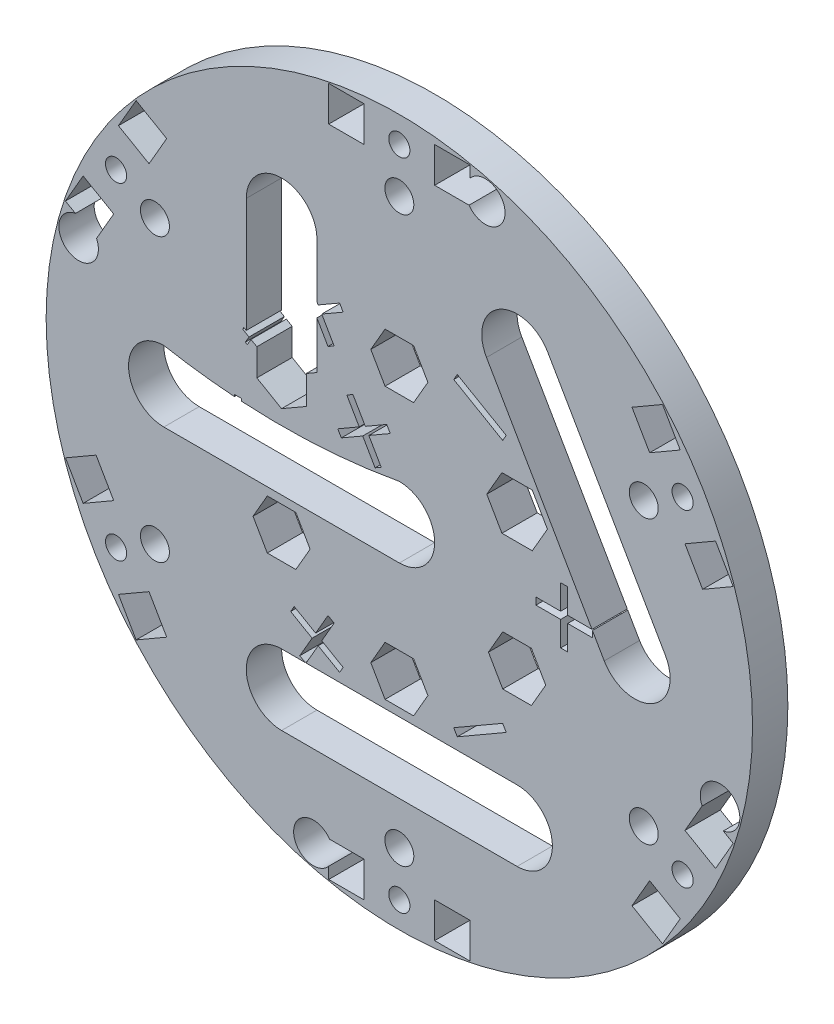
SolidWorks part; units mm, degrees
ref_plane "Plan de face" through (0, 0, 0) normal (0, 0, 1) x (1, 0, 0)
ref_plane "Plan de dessus" through (0, 0, 0) normal (0, 1, 0) x (1, 0, 0)
ref_plane "Plan de droite" through (0, 0, 0) normal (1, 0, 0) x (0, 0, -1)
sketch "Esquisse1" plane through (0, 0, 0) normal (0, 0, 1) x (1, 0, 0)
  line L0 (53.6751, 0) -> (-86.559, 0) construction
  line L1 (0, 50) -> (0, -56.2363) construction
  line L2 (0, 0) -> (70.5826, 40.7509) construction
  line L3 (0, 0) -> (-77.9761, 45.0195) construction
  line L4 (16.6667, 28.8675) -> (33.3333, 0) construction
  line L5 (20.9968, 31.3675) -> (37.6635, 2.5)
  line L6 (12.3365, 26.3675) -> (29.0032, -2.5)
  line L7 (16.6667, -28.8675) -> (-16.6667, -28.8675) construction
  line L8 (16.6667, -33.8675) -> (-16.6667, -33.8675)
  line L9 (16.6667, -23.8675) -> (-16.6667, -23.8675)
  line L10 (-33.3333, 0) -> (0, 0) construction
  line L11 (-21.6707, 12.5116) -> (-20.1709, 11.6468)
  line L12 (-33.3333, -5) -> (0, -5)
  line L13 (-16.6714, 9.6252) -> (-16.6667, 28.8675) construction
  line L14 (-21.6707, 12.5116) -> (-21.6667, 28.8687)
  line L15 (-11.6707, 12.5116) -> (-11.6667, 28.8663)
  line L16 (-13.1709, 11.6451) -> (-11.6707, 12.5116)
  line L17 (-12.6299, -9.6252) -> (-14.6507, -6.1252)
  line L18 (-14.6507, -6.1252) -> (-18.6921, -6.1252)
  line L19 (-18.6921, -6.1252) -> (-20.7128, -9.6252)
  line L20 (-20.7128, -9.6252) -> (-18.6921, -13.1252)
  line L21 (-18.6921, -13.1252) -> (-14.6507, -13.1252)
  line L22 (-14.6507, -13.1252) -> (-12.6299, -9.6252)
  line L23 (2.0207, -15.7328) -> (-2.0207, -15.7328)
  line L24 (-2.0207, -15.7328) -> (-4.0415, -19.2328)
  line L25 (-4.0415, -19.2328) -> (-2.0207, -22.7328)
  line L26 (-2.0207, -22.7328) -> (2.0207, -22.7328)
  line L27 (2.0207, -22.7328) -> (4.0415, -19.2328)
  line L28 (4.0415, -19.2328) -> (2.0207, -15.7328)
  line L29 (14.64, -6.1122) -> (12.6134, -9.6225)
  line L30 (12.6134, -9.6225) -> (14.64, -13.1328)
  line L31 (14.64, -13.1328) -> (18.6933, -13.1328)
  line L32 (18.6933, -13.1328) -> (20.72, -9.6225)
  line L33 (20.72, -9.6225) -> (18.6933, -6.1122)
  line L34 (18.6933, -6.1122) -> (14.64, -6.1122)
  line L35 (20.9633, 9.6242) -> (18.8164, 13.3427)
  line L36 (18.8164, 13.3427) -> (14.5227, 13.3427)
  line L37 (14.5227, 13.3427) -> (12.3758, 9.6242)
  line L38 (12.3758, 9.6242) -> (14.5227, 5.9057)
  line L39 (14.5227, 5.9057) -> (18.8164, 5.9057)
  line L40 (18.8164, 5.9057) -> (20.9633, 9.6242)
  line L41 (4.0415, 19.1653) -> (2.0207, 22.6653)
  line L42 (2.0207, 22.6653) -> (-2.0207, 22.6653)
  line L43 (-2.0207, 22.6653) -> (-4.0415, 19.1653)
  line L44 (-4.0415, 19.1653) -> (-2.0207, 15.6653)
  line L45 (-2.0207, 15.6653) -> (2.0207, 15.6653)
  line L46 (2.0207, 15.6653) -> (4.0415, 19.1653)
  line L47 (-20.1709, 11.6468) -> (-20.1719, 7.6054)
  line L48 (-20.1719, 7.6054) -> (-16.6724, 5.5838)
  line L49 (-16.6724, 5.5838) -> (-13.1719, 7.6036)
  line L50 (-13.1719, 7.6036) -> (-13.1709, 11.6451)
  line L52 (-16.6704, 13.6667) -> (-20.1709, 11.6468) [skipped]
  line L53 (-13.1709, 11.6451) -> (-16.6704, 13.6667) [skipped]
  circle A0 centre (0, 0) radius 50
  circle A1 centre (33.3333, 0) radius 16.6667 construction
  circle A2 centre (16.6667, -28.8675) radius 16.6667 construction
  circle A3 centre (-16.6667, -28.8675) radius 16.6667 construction
  circle A4 centre (-33.3333, 0) radius 16.6667 construction
  circle A5 centre (-16.6667, 28.8675) radius 16.6667 construction
  circle A6 centre (16.6667, 28.8675) radius 16.6667 construction
  circle A7 centre (-34.5978, 19.9751) radius 2.05
  circle A8 centre (0, 39.9502) radius 2.05
  circle A9 centre (34.5978, 19.9751) radius 2.05
  circle A10 centre (34.5978, -19.9751) radius 2.05
  circle A11 centre (0, -39.9502) radius 2.05
  circle A12 centre (-34.5978, -19.9751) radius 2.05
  arc A13 (20.9968, 31.3675) -> (12.3365, 26.3675) centre (16.6667, 28.8675) ccw
  circle A14 centre (0, 0) radius 16.6667 construction
  circle A15 centre (16.6667, -9.6225) radius 3.5103 construction
  circle A17 centre (-16.6714, -9.6252) radius 3.5 construction
  arc A18 (16.6667, -33.8675) -> (16.6667, -23.8675) centre (16.6667, -28.8675) ccw
  arc A20 (-33.3333, 5) -> (-33.3333, -5) centre (-33.3333, 0) ccw
  arc A22 (-16.6667, -23.8675) -> (-16.6667, -33.8675) centre (-16.6667, -28.8675) ccw
  circle A23 centre (0, -19.2328) radius 3.5 construction
  arc A24 (29.0032, -2.5) -> (37.6635, 2.5) centre (33.3333, 0) ccw
  circle A25 centre (16.6696, 9.6242) radius 3.7185 construction
  circle A26 centre (0, 19.1653) radius 3.5 construction
  arc A27 (0, -5) -> (0, 5) centre (0, 0) ccw
  arc A28 (-33.3333, 5) -> (0, 5) centre (-16.6667, 95.7057) ccw
  circle A29 centre (-16.6714, 9.6252) radius 3.5 construction
  arc A35 (-11.6667, 28.8663) -> (-21.6667, 28.8687) centre (-16.6667, 28.8675) ccw
  point P20 (0, 0)
  point P30 (0, 0)
  point P36 (25, 14.4338)
  point P40 (0, -28.8675)
  point P44 (-16.669, 19.2464)
  point P48 (-16.6667, 0)
  point P54 (0, 0)
  point P60 (0, 0)
  point P117 (0, 0)
  line B0 (37.597, -27.4801) -> (42.597, -18.8199) construction
  line B1 (35.4319, -26.2301) -> (32.9319, -30.5603)
  line B2 (35.4319, -26.2301) -> (39.762, -28.7301)
  line B3 (39.762, -28.7301) -> (37.262, -33.0603)
  line B4 (32.9319, -30.5603) -> (37.262, -33.0603)
  line B5 (40.4319, -17.5699) -> (42.9319, -13.2397)
  line B6 (40.4319, -17.5699) -> (44.762, -20.0699)
  line B7 (44.762, -20.0699) -> (47.262, -15.7397)
  line B8 (42.9319, -13.2397) -> (47.262, -15.7397)
  circle B9 centre (40.097, -23.15) radius 1.5
  line B10 (-5, -46.3) -> (5, -46.3) construction
  line B11 (-5, -43.8) -> (-10, -43.8)
  line B12 (-5, -43.8) -> (-5, -48.8)
  line B13 (-5, -48.8) -> (-10, -48.8)
  line B14 (-10, -43.8) -> (-10, -48.8)
  line B15 (5, -43.8) -> (10, -43.8)
  line B16 (5, -43.8) -> (5, -48.8)
  line B17 (5, -48.8) -> (10, -48.8)
  line B18 (10, -43.8) -> (10, -48.8)
  circle B19 centre (0, -46.3) radius 1.5
  line B20 (-42.597, -18.8199) -> (-37.597, -27.4801) construction
  line B21 (-40.4319, -17.5699) -> (-42.9319, -13.2397)
  line B22 (-40.4319, -17.5699) -> (-44.762, -20.0699)
  line B23 (-44.762, -20.0699) -> (-47.262, -15.7397)
  line B24 (-42.9319, -13.2397) -> (-47.262, -15.7397)
  line B25 (-35.4319, -26.2301) -> (-32.9319, -30.5603)
  line B26 (-35.4319, -26.2301) -> (-39.762, -28.7301)
  line B27 (-39.762, -28.7301) -> (-37.262, -33.0603)
  line B28 (-32.9319, -30.5603) -> (-37.262, -33.0603)
  circle B29 centre (-40.097, -23.15) radius 1.5
  line B30 (-37.597, 27.4801) -> (-42.597, 18.8199) construction
  line B31 (-35.4319, 26.2301) -> (-32.9319, 30.5603)
  line B32 (-35.4319, 26.2301) -> (-39.762, 28.7301)
  line B33 (-39.762, 28.7301) -> (-37.262, 33.0603)
  line B34 (-32.9319, 30.5603) -> (-37.262, 33.0603)
  line B35 (-40.4319, 17.5699) -> (-42.9319, 13.2397)
  line B36 (-40.4319, 17.5699) -> (-44.762, 20.0699)
  line B37 (-44.762, 20.0699) -> (-47.262, 15.7397)
  line B38 (-42.9319, 13.2397) -> (-47.262, 15.7397)
  circle B39 centre (-40.097, 23.15) radius 1.5
  line B40 (5, 46.3) -> (-5, 46.3) construction
  line B41 (5, 43.8) -> (10, 43.8)
  line B42 (5, 43.8) -> (5, 48.8)
  line B43 (5, 48.8) -> (10, 48.8)
  line B44 (10, 43.8) -> (10, 48.8)
  line B45 (-5, 43.8) -> (-10, 43.8)
  line B46 (-5, 43.8) -> (-5, 48.8)
  line B47 (-5, 48.8) -> (-10, 48.8)
  line B48 (-10, 43.8) -> (-10, 48.8)
  circle B49 centre (0, 46.3) radius 1.5
  line B50 (42.597, 18.8199) -> (37.597, 27.4801) construction
  line B51 (40.4319, 17.5699) -> (42.9319, 13.2397)
  line B52 (40.4319, 17.5699) -> (44.762, 20.0699)
  line B53 (44.762, 20.0699) -> (47.262, 15.7397)
  line B54 (42.9319, 13.2397) -> (47.262, 15.7397)
  line B55 (35.4319, 26.2301) -> (32.9319, 30.5603)
  line B56 (35.4319, 26.2301) -> (39.762, 28.7301)
  line B57 (39.762, 28.7301) -> (37.262, 33.0603)
  line B58 (32.9319, 30.5603) -> (37.262, 33.0603)
  circle B59 centre (40.097, 23.15) radius 1.5
  dimension "D1" = 6
  dimension "D2" = 30
  dimension "D4" = 6
  dimension "D5" = 10
  dimension "D6" = 46.3
  dimension "D3" = 30
  dimension "D7" = 6
sketch_block_instance "Trou M3 plots 5mm-1"
sketch_block "Trou M3 plots 5mm" parameters "D2"=3, "D1"=5, "D3"=5, "D4"=10
sketch_block_instance "Trou M3 plots 5mm-3"
sketch_block_instance "Trou M3 plots 5mm-4"
sketch_block_instance "Trou M3 plots 5mm-5"
sketch_block_instance "Trou M3 plots 5mm-6"
sketch_block_instance "Trou M3 plots 5mm-7"
extrude "Boss.-Extru.1" add sketch "Esquisse1" along normal blind 5
sketch "Sketch2" plane through (0, 0, 5) normal (0, 0, 1) x (1, 0, 0)
  line L0 (53.6751, 0) -> (-86.559, 0) construction
  line L1 (-173205.0808, -100000) -> (173275.6634, 100040.7509) construction
  arc A0 (-50, 0) -> (-25, -14.4338) centre (-33.3333, 0) ccw
  circle A1 centre (0, 0) radius 50 construction
  arc A2 (-25, -14.4338) -> (-25, -43.3013) centre (-16.6667, -28.8675) ccw
  arc A3 (-25, -43.3013) -> (-50, 0) centre (0, 0) ccw
extrude "Cut-Extrude1" [suppressed] cut sketch "Sketch2" against normal through all contours A2 A3 A0
sketch "Sketch3" plane through (0, 0, 5) normal (0, 0, 1) x (1, 0, 0)
  line L0 (53.6751, 0) -> (-86.559, 0) construction
  line L6 (16.6667, 28.8675) -> (-16.6667, -28.8675) construction
  line L7 (-23.3333, 4) -> (-22.3333, 4)
  line L8 (-23.3333, 4) -> (-23.3333, -4)
  line L9 (-23.3333, -4) -> (-22.3333, -4)
  line L10 (-22.3333, 4) -> (-22.3333, -4)
  line L11 (-16.6667, 28.8675) -> (16.6667, -28.8675) construction
  line L12 (-13.2337, 23.9214) -> (-14.0997, 23.4214)
  line L13 (-14.0997, 23.4214) -> (-12.3497, 20.3903)
  line L14 (-12.3497, 20.3903) -> (-15.3808, 18.6403)
  line L15 (-15.3808, 18.6403) -> (-14.8808, 17.7742)
  line L16 (-14.8808, 17.7742) -> (-11.8497, 19.5242)
  line L17 (-11.8497, 19.5242) -> (-10.0997, 16.4932)
  line L18 (-10.0997, 16.4932) -> (-9.2337, 16.9932)
  line L19 (-9.2337, 16.9932) -> (-10.9837, 20.0242)
  line L20 (-10.9837, 20.0242) -> (-7.9526, 21.7742)
  line L21 (-7.9526, 21.7742) -> (-8.4526, 22.6403)
  line L22 (-8.4526, 22.6403) -> (-11.4837, 20.8903)
  line L23 (-11.4837, 20.8903) -> (-13.2337, 23.9214)
  line L24 (-16.2531, 17.5593) -> (-5.3419, 23.8588) construction
  line L25 (-14.6252, 25.3316) -> (-8.4936, 14.7114) construction
  line L26 (15.1308, 18.2073) -> (14.6308, 17.3412)
  line L27 (15.1308, 18.2073) -> (8.2026, 22.2073)
  line L28 (8.2026, 22.2073) -> (7.7026, 21.3412)
  line L29 (14.6308, 17.3412) -> (7.7026, 21.3412)
  line L30 (8.2026, -22.2073) -> (7.7026, -21.3412)
  line L31 (8.2026, -22.2073) -> (15.1308, -18.2073)
  line L32 (15.1308, -18.2073) -> (14.6308, -17.3412)
  line L33 (7.7026, -21.3412) -> (14.6308, -17.3412)
  line L34 (27.3333, -0.5) -> (27.3333, 0.5)
  line L35 (27.3333, 0.5) -> (23.8333, 0.5)
  line L36 (23.8333, 0.5) -> (23.8333, 4)
  line L37 (23.8333, 4) -> (22.8333, 4)
  line L38 (22.8333, 4) -> (22.8333, 0.5)
  line L39 (22.8333, 0.5) -> (19.3333, 0.5)
  line L40 (19.3333, 0.5) -> (19.3333, -0.5)
  line L41 (19.3333, -0.5) -> (22.8333, -0.5)
  line L42 (22.8333, -0.5) -> (22.8333, -4)
  line L43 (22.8333, -4) -> (23.8333, -4)
  line L44 (23.8333, -4) -> (23.8333, -0.5)
  line L45 (23.8333, -0.5) -> (27.3333, -0.5)
  line L46 (-14.0997, -23.4214) -> (-13.2337, -23.9214)
  line L47 (-13.2337, -23.9214) -> (-11.4837, -20.8903)
  line L48 (-11.4837, -20.8903) -> (-8.4526, -22.6403)
  line L49 (-8.4526, -22.6403) -> (-7.9526, -21.7742)
  line L50 (-7.9526, -21.7742) -> (-10.9837, -20.0242)
  line L51 (-10.9837, -20.0242) -> (-9.2337, -16.9932)
  line L52 (-9.2337, -16.9932) -> (-10.0997, -16.4932)
  line L53 (-10.0997, -16.4932) -> (-11.8497, -19.5242)
  line L54 (-11.8497, -19.5242) -> (-14.8808, -17.7742)
  line L55 (-14.8808, -17.7742) -> (-15.3808, -18.6403)
  line L56 (-15.3808, -18.6403) -> (-12.3497, -20.3903)
  line L57 (-12.3497, -20.3903) -> (-14.0997, -23.4214)
  line L58 (-21.8333, 14.2784) -> (-24.4284, 9.7836) construction
  line L59 (173205.0808, -100000) -> (-173283.0568, 100045.0195) construction
  line L60 (-7.433, 11.8744) -> (-5.683, 8.8433)
  line L61 (-6.567, 12.3744) -> (-7.433, 11.8744)
  line L62 (-7.8805, 13.6494) -> (-1.7489, 3.0291) construction
  line L63 (-2.567, 5.4462) -> (-4.317, 8.4772)
  line L64 (-1.2859, 10.2272) -> (-1.7859, 11.0933)
  line L65 (-3.433, 4.9462) -> (-2.567, 5.4462)
  line L66 (-4.317, 8.4772) -> (-1.2859, 10.2272)
  line L67 (-8.7141, 7.0933) -> (-8.2141, 6.2272)
  line L68 (-8.2141, 6.2272) -> (-5.183, 7.9772)
  line L69 (-4.817, 9.3433) -> (-6.567, 12.3744)
  line L70 (-1.7859, 11.0933) -> (-4.817, 9.3433)
  line L71 (-5.183, 7.9772) -> (-3.433, 4.9462)
  line L72 (-5.683, 8.8433) -> (-8.7141, 7.0933)
  line L73 (-9.0607, 6.3158) -> (-0.8395, 11.0623) construction
  line L74 (-173205.0808, -100000) -> (173275.6634, 100040.7509) construction
  text T0 "+"
  point P2 (-8.4641, 6.6603)
  point P4 (-1.5359, 10.6603)
  point P36 (-8.2026, 22.2073)
  point P39 (-13.6667, 23.6714)
  point P51 (0, 0)
  point P75 (0, 0)
  point P85 (-23.3333, 0)
  point P92 (-1.5413, 10.6572)
  dimension "D2" = 1
  dimension "D3" = 10
  dimension "D4" = 1
  dimension "D5" = 8
  dimension "D6" = 10
  dimension "D7" = 1
  dimension "D8" = 1
  dimension "D9" = 8
  dimension "D10" = 8
  dimension "D11" = 4
  dimension "D12" = 4
  dimension "D13" = 10
  dimension "D16" = 1
  dimension "D14" = 3
  dimension "D15" = 3
extrude "Cut-Extrude2" cut sketch "Sketch3" against normal blind 10
sketch "Sketch4" plane through (0, 0, 5) normal (0, 0, 1) x (1, 0, 0)
  line L0 (-0.2034, -0.7591) -> (-16.9538, -63.2725) construction
  line L1 (0, 0) -> (0, -46.3) construction
  circle A0 centre (-12.1645, -45.3985) radius 2.8
  circle A1 centre (-45.3985, 12.1645) radius 2.8
  circle A2 centre (12.1645, 45.3985) radius 2.8
  circle A3 centre (45.3985, -12.1645) radius 2.8
  point P18 (0, 0)
  dimension "D2" = 47
  dimension "D1" = 15
  dimension "D3" = 4
extrude "Cut-Extrude4" cut sketch "Sketch4" against normal blind 10
